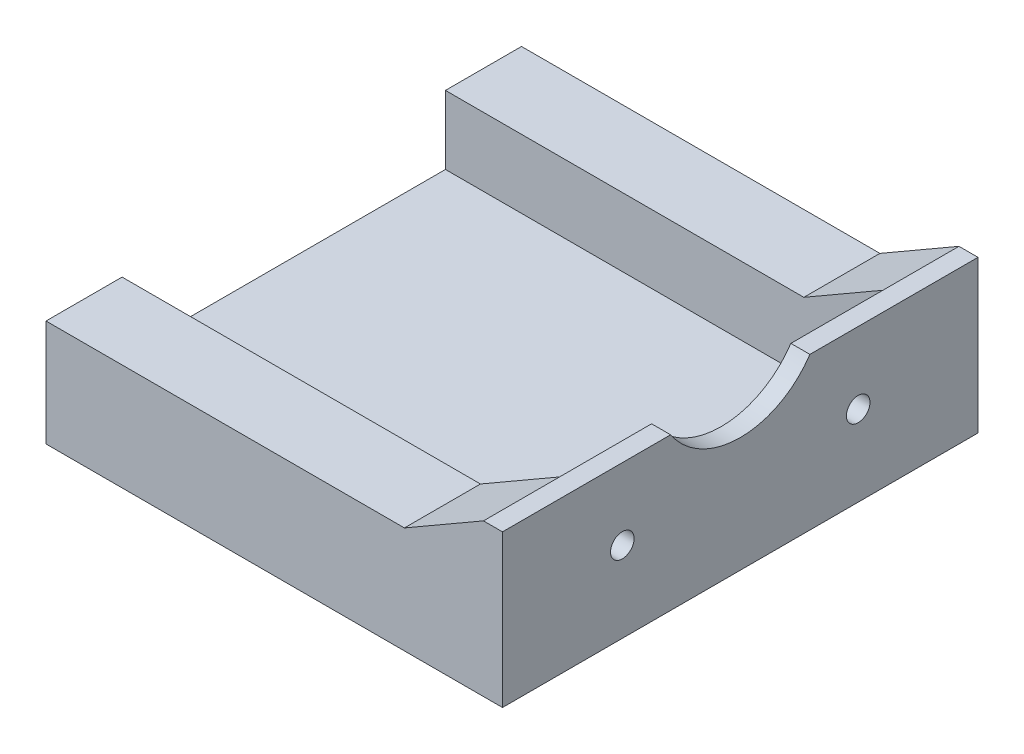
SolidWorks part; units mm, degrees
ref_plane "Front Plane" through (0, 0, 0) normal (0, 0, 1) x (1, 0, 0)
ref_plane "Top Plane" through (0, 0, 0) normal (0, 1, 0) x (1, 0, 0)
ref_plane "Right Plane" through (0, 0, 0) normal (1, 0, 0) x (0, 0, -1)
sketch "Sketch1" plane through (0, 0, 0) normal (0, 1, 0) x (1, 0, 0)
  line L1 (0, 0) -> (60, 0)
  line L2 (0, 0) -> (0, 62.5)
  line L3 (0, 62.5) -> (60, 62.5)
  line L4 (60, 0) -> (60, 62.5)
  dimension "D1" = 62.5
  dimension "D2" = 60
extrude "Boss-Extrude1" add sketch "Sketch1" along normal blind 5
sketch "Sketch2" plane through (60, 0, 0) normal (1, 0, 0) x (0, 0, -1)
  line L0 (62.5, 5) -> (62.5, 0) construction
  line L1 (0, 0) -> (62.5, 0)
  line L2 (0, 0) -> (0, 20)
  line L3 (0, 20) -> (62.5, 20)
  line L4 (62.5, 0) -> (62.5, 20)
  line L5 (0, 5) -> (62.5, 5) construction
  circle A0 centre (31.25, 26.1) radius 11
  point P7 (31.25, 20)
  line M4 (62.5, 5) -> (0, 5)
  dimension "D1" = 21.1
  dimension "D3" = 22
  dimension "D2" = 20
extrude "Boss-Extrude2" add sketch "Sketch2" against normal blind 2.5 contours A0 L3 L2 L4 M4
sketch "Sketch3" plane through (0, 0, 0) normal (0, 0, 1) x (1, 0, 0)
  line L0 (57.5, 20) -> (31.5192, 5)
  line L1 (0, 5) -> (57.5, 5) construction
  line L2 (31.5192, 5) -> (57.5, 5)
  line L3 (57.5, 5) -> (57.5, 20)
  dimension "D1" = 30
extrude "Boss-Extrude3" add sketch "Sketch3" against normal blind 10
ref_plane "Plane1" through (0, 0, -31.25) normal (0, 0, 1) x (1, 0, 0)
sketch "Sketch8" plane through (0, 0, 0) normal (0, 0, -1) x (-1, 0, 0)
  line L2 (-47.1077, 14) -> (-47.1077, 5)
  line L3 (-47.1077, 5) -> (-33.3872, 5)
  line L6 (-57.5, 5) -> (0, 5) construction
  line L7 (-24.1565, 5) -> (-33.3872, 5)
  line L8 (-57.5, 20) -> (-31.5192, 5) construction
  line L9 (-24.1565, 5) -> (0, 5)
  line L14 (0, 5) -> (0, 0) construction
  line L15 (-47.1077, 14) -> (0, 14)
  line L16 (0, 14) -> (0, 5)
  dimension "D2" = 9
  dimension "D3" = 0
extrude "Boss-Extrude4" add sketch "Sketch8" along normal blind 10 contours L7 L3 L2 L15 L16 L9
mirror "Mirror1" about plane through (0, 0, -31.25) normal (0, 0, 1) of "Boss-Extrude4", "Boss-Extrude3"
sketch "Sketch4" plane through (60, 0, 0) normal (1, 0, 0) x (0, 0, -1)
  circle A1 centre (15.75, 10.6) radius 1.55
  circle A2 centre (46.75, 10.6) radius 1.55
  dimension "D1" = 3.1
  dimension "D2" = 3.1
extrude "Cut-Extrude1" cut sketch "Sketch4" against normal blind 10
hole_wizard "M5 Clearance Hole1" positions "Sketch5" profile "Sketch7" hole size "M5" standard "ISO" end condition through all
sketch "Sketch5" plane through (0, 0, 0) normal (0, -1, 0) x (-1, 0, 0)
  line L0 (-60, 62.5) -> (0, 62.5) construction
  line L1 (0, 0) -> (-60, 0) construction
  line L2 (0, 62.5) -> (0, 0) construction
  line L3 (-60, 0) -> (-60, 62.5) construction
  point P0 (-40, 57.5)
  point P2 (-10, 57.5)
  point P4 (-40, 5)
  point P6 (-10, 5)
  dimension "D1" = 5
  dimension "D2" = 5
  dimension "D3" = 10
  dimension "D4" = 10
  dimension "D5" = 20
  dimension "D6" = 20
sketch "Sketch7" plane through (40, 0, -57.5) normal (1, 0, 0) x (0, 0, -1)
  line L0 (0, 0) -> (0, 20)
  line L1 (0, 20) -> (3.2, 20)
  line L2 (3.2, 20) -> (3.2, 0)
  line L5 (3.2, 0) -> (0, 0)
  line L11 (0, -6.35) -> (0, 107.95) construction
  dimension "Thru Hole Dia." = 6.4
  dimension "Thru Hole Depth" = 20
sketch "Sketch11" plane through (0, 14, 0) normal (0, 1, 0) x (1, 0, 0)
  line L0 (47.1077, 62.5) -> (0, 62.5) construction
  line L1 (0, 62.5) -> (47.1077, 62.5)
  line L2 (0, 62.5) -> (0, 52.5)
  line L3 (0, 52.5) -> (47.1077, 52.5)
  line L4 (47.1077, 62.5) -> (47.1077, 52.5)
  line L5 (47.1077, 52.5) -> (47.1077, 62.5) construction
  line L6 (57.5, 52.5) -> (47.1077, 52.5) construction
  line L7 (47.1077, 0) -> (0, 0) construction
  line L8 (0, 0) -> (47.1077, 0)
  line L9 (0, 0) -> (0, 10)
  line L10 (0, 10) -> (47.1077, 10)
  line L11 (47.1077, 0) -> (47.1077, 10)
  line L12 (47.1077, 10) -> (47.1077, 0) construction
extrude "Boss-Extrude5" add sketch "Sketch11" against normal blind 2.5
